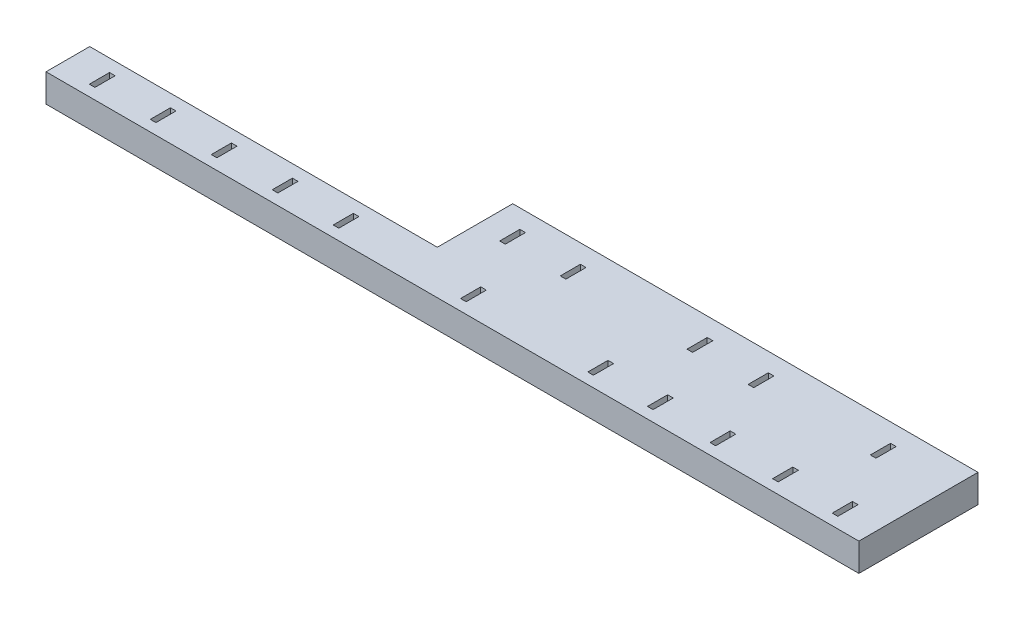
SolidWorks part; units mm, degrees
ref_plane "Front Plane" through (0, 0, 0) normal (0, 0, 1) x (1, 0, 0)
ref_plane "Top Plane" through (0, 0, 0) normal (0, 1, 0) x (1, 0, 0)
ref_plane "Right Plane" through (0, 0, 0) normal (1, 0, 0) x (0, 0, -1)
sketch "Sketch1" plane through (0, 0, 0) normal (0, 1, 0) x (1, 0, 0)
  line L0 (-72.5, 0) -> (72.5, 0) construction
  line L1 (-72.5, -17.5) -> (72.5, -17.5)
  line L2 (-72.5, -17.5) -> (-72.5, 17.5)
  line L3 (-72.5, 17.5) -> (72.5, 17.5)
  line L4 (72.5, -17.5) -> (72.5, 17.5)
  line L5 (-72.5, -17.5) -> (72.5, 17.5) construction
  line L6 (-72.5, 17.5) -> (72.5, -17.5) construction
  line L7 (-0.5, -1.8) -> (0.5, -1.8)
  line L8 (-0.5, -1.8) -> (-0.5, 1.8)
  line L9 (-0.5, 1.8) -> (0.5, 1.8)
  line L10 (0.5, -1.8) -> (0.5, 1.8)
  line L11 (-0.5, -1.8) -> (0.5, 1.8) construction
  line L12 (-0.5, 1.8) -> (0.5, -1.8) construction
  line L14 (-23.22, -1.8) -> (-22.22, -1.8)
  line L15 (-23.22, -1.8) -> (-23.22, 1.8)
  line L16 (-23.22, 1.8) -> (-22.22, 1.8)
  line L17 (-22.22, -1.8) -> (-22.22, 1.8)
  line L18 (-23.22, -1.8) -> (-22.22, 1.8) construction
  line L19 (-23.22, 1.8) -> (-22.22, -1.8) construction
  line L20 (-34.095, -1.8) -> (-33.095, -1.8)
  line L21 (-34.095, -1.8) -> (-34.095, 1.8)
  line L22 (-34.095, 1.8) -> (-33.095, 1.8)
  line L23 (-33.095, -1.8) -> (-33.095, 1.8)
  line L24 (-34.095, -1.8) -> (-33.095, 1.8) construction
  line L25 (-34.095, 1.8) -> (-33.095, -1.8) construction
  line L26 (-44.97, -1.8) -> (-43.97, -1.8)
  line L27 (-44.97, -1.8) -> (-44.97, 1.8)
  line L28 (-44.97, 1.8) -> (-43.97, 1.8)
  line L29 (-43.97, -1.8) -> (-43.97, 1.8)
  line L30 (-44.97, -1.8) -> (-43.97, 1.8) construction
  line L31 (-44.97, 1.8) -> (-43.97, -1.8) construction
  line L32 (-55.845, -1.8) -> (-54.845, -1.8)
  line L33 (-55.845, -1.8) -> (-55.845, 1.8)
  line L34 (-55.845, 1.8) -> (-54.845, 1.8)
  line L35 (-54.845, -1.8) -> (-54.845, 1.8)
  line L36 (-55.845, -1.8) -> (-54.845, 1.8) construction
  line L37 (-55.845, 1.8) -> (-54.845, -1.8) construction
  line L38 (-66.72, -1.8) -> (-65.72, -1.8)
  line L39 (-66.72, -1.8) -> (-66.72, 1.8)
  line L40 (-66.72, 1.8) -> (-65.72, 1.8)
  line L41 (-65.72, -1.8) -> (-65.72, 1.8)
  line L42 (-66.72, -1.8) -> (-65.72, 1.8) construction
  line L43 (-66.72, 1.8) -> (-65.72, -1.8) construction
  line L44 (22.2, -1.8) -> (23.2, -1.8)
  line L45 (22.2, -1.8) -> (22.2, 1.8)
  line L46 (22.2, 1.8) -> (23.2, 1.8)
  line L47 (23.2, -1.8) -> (23.2, 1.8)
  line L48 (22.2, -1.8) -> (23.2, 1.8) construction
  line L49 (22.2, 1.8) -> (23.2, -1.8) construction
  line L50 (32.837, -1.8) -> (33.837, -1.8)
  line L51 (32.837, -1.8) -> (32.837, 1.8)
  line L52 (32.837, 1.8) -> (33.837, 1.8)
  line L53 (33.837, -1.8) -> (33.837, 1.8)
  line L54 (32.837, -1.8) -> (33.837, 1.8) construction
  line L55 (32.837, 1.8) -> (33.837, -1.8) construction
  line L56 (43.999, -1.8) -> (44.999, -1.8)
  line L57 (43.999, -1.8) -> (43.999, 1.8)
  line L58 (43.999, 1.8) -> (44.999, 1.8)
  line L59 (44.999, -1.8) -> (44.999, 1.8)
  line L60 (43.999, -1.8) -> (44.999, 1.8) construction
  line L61 (43.999, 1.8) -> (44.999, -1.8) construction
  line L62 (55.161, -1.8) -> (56.161, -1.8)
  line L63 (55.161, -1.8) -> (55.161, 1.8)
  line L64 (55.161, 1.8) -> (56.161, 1.8)
  line L65 (56.161, -1.8) -> (56.161, 1.8)
  line L66 (55.161, -1.8) -> (56.161, 1.8) construction
  line L67 (55.161, 1.8) -> (56.161, -1.8) construction
  line L68 (65.798, -1.8) -> (66.798, -1.8)
  line L69 (65.798, -1.8) -> (65.798, 1.8)
  line L70 (65.798, 1.8) -> (66.798, 1.8)
  line L71 (66.798, -1.8) -> (66.798, 1.8)
  line L72 (65.798, -1.8) -> (66.798, 1.8) construction
  line L73 (65.798, 1.8) -> (66.798, -1.8) construction
  line L74 (-5.9, 10.58) -> (-4.9, 10.58)
  line L75 (-5.9, 10.58) -> (-5.9, 14.18)
  line L76 (-5.9, 14.18) -> (-4.9, 14.18)
  line L77 (-4.9, 10.58) -> (-4.9, 14.18)
  line L78 (-5.9, 10.58) -> (-4.9, 14.18) construction
  line L79 (-5.9, 14.18) -> (-4.9, 10.58) construction
  line L80 (4.9, 10.58) -> (5.9, 10.58)
  line L81 (4.9, 10.58) -> (4.9, 14.18)
  line L82 (4.9, 14.18) -> (5.9, 14.18)
  line L83 (5.9, 10.58) -> (5.9, 14.18)
  line L84 (4.9, 10.58) -> (5.9, 14.18) construction
  line L85 (4.9, 14.18) -> (5.9, 10.58) construction
  line L86 (27.519, 10.58) -> (28.519, 10.58)
  line L87 (27.519, 10.58) -> (27.519, 14.18)
  line L88 (27.519, 14.18) -> (28.519, 14.18)
  line L89 (28.519, 10.58) -> (28.519, 14.18)
  line L90 (27.519, 10.58) -> (28.519, 14.18) construction
  line L91 (27.519, 14.18) -> (28.519, 10.58) construction
  line L92 (38.418, 10.58) -> (39.418, 10.58)
  line L93 (38.418, 10.58) -> (38.418, 14.18)
  line L94 (38.418, 14.18) -> (39.418, 14.18)
  line L95 (39.418, 10.58) -> (39.418, 14.18)
  line L96 (38.418, 10.58) -> (39.418, 14.18) construction
  line L97 (38.418, 14.18) -> (39.418, 10.58) construction
  line L98 (60.217, 10.58) -> (61.217, 10.58)
  line L99 (60.217, 10.58) -> (60.217, 14.18)
  line L100 (60.217, 14.18) -> (61.217, 14.18)
  line L101 (61.217, 10.58) -> (61.217, 14.18)
  line L102 (60.217, 10.58) -> (61.217, 14.18) construction
  line L103 (60.217, 14.18) -> (61.217, 10.58) construction
  point P0 (0, 0)
  point P6 (0, 0)
  point P11 (-22.72, 0)
  point P14 (0, 0)
  point P19 (-33.595, 0)
  point P24 (-44.47, 0)
  point P29 (-55.345, 0)
  point P34 (-66.22, 0)
  point P39 (22.7, 0)
  point P44 (33.337, 0)
  point P49 (44.499, 0)
  point P54 (55.661, 0)
  point P59 (66.298, 0)
  point P64 (-5.4, 12.38)
  point P69 (5.4, 12.38)
  point P74 (28.019, 12.38)
  point P79 (38.918, 12.38)
  point P84 (60.717, 12.38)
  dimension "D1" = 1
  dimension "D2" = 3.6
  dimension "D3" = 35
  dimension "D4" = 145
  dimension "D5" = 22.72
  dimension "D6" = 10.875
  dimension "D7" = 10.875
  dimension "D8" = 10.875
  dimension "D9" = 10.875
  dimension "D10" = 22.7
  dimension "D11" = 10.637
  dimension "D12" = 11.162
  dimension "D13" = 11.162
  dimension "D14" = 10.637
  dimension "D15" = 12.38
  dimension "D16" = 5.4
  dimension "D17" = 5.4
  dimension "D18" = 12.38
  dimension "D19" = 12.38
  dimension "D20" = 5.319
  dimension "D21" = 5.581
  dimension "D22" = 12.38
  dimension "D23" = 12.38
  dimension "D24" = 5.056
extrude "Boss-Extrude1" add sketch "Sketch1" along normal blind 5
sketch "Sketch2" plane through (0, 5, 0) normal (0, 1, 0) x (1, 0, 0)
  line L0 (72.5, -17.5) -> (72.5, 17.5) construction
  line L1 (-72.5, -17.5) -> (72.5, -17.5)
  line L2 (-72.5, -17.5) -> (-72.5, -3.7477)
  line L3 (-72.5, -3.7477) -> (72.5, -3.7477)
  line L4 (72.5, -17.5) -> (72.5, -3.7477)
  line L6 (-72.5, 17.5) -> (-10.4937, 17.5)
  line L7 (-72.5, 17.5) -> (-72.5, 4.0476)
  line L8 (-72.5, 4.0476) -> (-10.4937, 4.0476)
  line L9 (-10.4937, 17.5) -> (-10.4937, 4.0476)
extrude "Cut-Extrude1" cut sketch "Sketch2" against normal up to next
sketch "Sketch4" plane through (0, 0, 0) normal (0, -1, 0) x (1, 0, 0)
  circle A0 centre (0, 0) radius 1.9
  circle A1 centre (-5.4, -12.38) radius 1.9
  circle A2 centre (-22.72, 0) radius 1.9
  circle A3 centre (-33.595, 0) radius 1.9
  circle A4 centre (-44.47, 0) radius 1.9
  circle A5 centre (-55.345, 0) radius 1.9
  circle A6 centre (-66.22, 0) radius 1.9
  circle A7 centre (5.4, -12.38) radius 1.9
  circle A8 centre (22.7, 0) radius 1.9
  circle A9 centre (33.337, 0) radius 1.9
  circle A10 centre (44.499, 0) radius 1.9
  circle A11 centre (55.661, 0) radius 1.9
  circle A12 centre (66.298, 0) radius 1.9
  circle A13 centre (28.019, -12.38) radius 1.9
  circle A14 centre (38.918, -12.38) radius 1.9
  circle A15 centre (60.717, -12.38) radius 1.9
  dimension "D1" = 3.8
extrude "Cut-Extrude2" cut sketch "Sketch4" against normal blind 3
